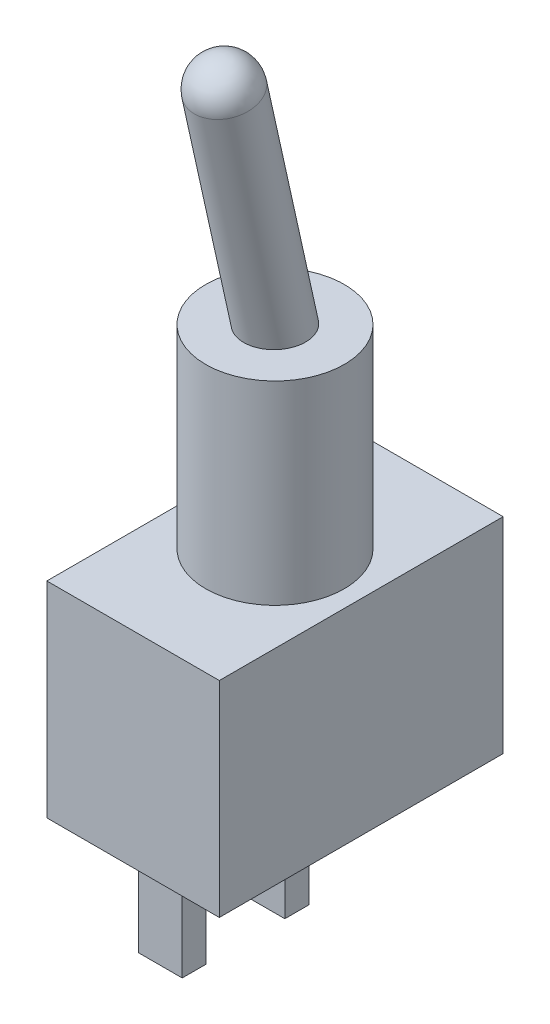
SolidWorks part; units mm, degrees
ref_plane "Front Plane" through (0, 0, 0) normal (0, 0, 1) x (1, 0, 0)
ref_plane "Top Plane" through (0, 0, 0) normal (0, 1, 0) x (1, 0, 0)
ref_plane "Right Plane" through (0, 0, 0) normal (1, 0, 0) x (0, 0, -1)
sketch "Sketch1" plane through (0, 0, 0) normal (0, 1, 0) x (1, 0, 0)
  line L1 (-3.95, 6.5) -> (3.95, 6.5)
  line L2 (-3.95, 6.5) -> (-3.95, -6.5)
  line L3 (-3.95, -6.5) -> (3.95, -6.5)
  line L4 (3.95, 6.5) -> (3.95, -6.5)
  line L5 (-3.95, 6.5) -> (3.95, -6.5) construction
  line L6 (-3.95, -6.5) -> (3.95, 6.5) construction
  point P0 (0, 0)
  dimension "D1" = 13
  dimension "D2" = 7.9
extrude "Boss-Extrude1" add sketch "Sketch1" against normal blind 9.4
sketch "Sketch2" plane through (0, -9.4, 0) normal (0, -1, 0) x (1, 0, 0)
  line L1 (-1, 5.25) -> (1, 5.25)
  line L2 (-1, 5.25) -> (-1, 4.15)
  line L3 (-1, 4.15) -> (1, 4.15)
  line L4 (1, 5.25) -> (1, 4.15)
  line L5 (-1, 5.25) -> (1, 4.15) construction
  line L6 (-1, 4.15) -> (1, 5.25) construction
  line L7 (-1, -0.55) -> (1, -0.55)
  line L8 (-1, -0.55) -> (-1, 0.55)
  line L9 (-1, 0.55) -> (1, 0.55)
  line L10 (1, -0.55) -> (1, 0.55)
  line L11 (-1, -0.55) -> (1, 0.55) construction
  line L12 (-1, 0.55) -> (1, -0.55) construction
  point P0 (0, 4.7)
  point P5 (0, 0)
  point P10 (0, 0)
  dimension "D1" = 1.1
  dimension "D2" = 2
  dimension "D3" = 4.7
extrude "Boss-Extrude2" add sketch "Sketch2" along normal blind 4.5
sketch "Sketch3" plane through (0, 0, 0) normal (0, 1, 0) x (1, 0, 0)
  circle A0 centre (0, 0) radius 3.175
  dimension "D1" = 6.35
extrude "Boss-Extrude3" add sketch "Sketch3" along normal blind 8.9
sketch "Sketch4" plane through (0, 0, 0) normal (1, 0, 0) x (0, 0, -1)
  line L0 (0, 8.9) -> (-2.3278, 19.4) construction
  line L1 (3.175, 8.9) -> (-3.175, 8.9) construction
  line L2 (0, 8.9) -> (0, 19.4) construction
  line L3 (0, 8.9) -> (1.434, 8.9)
  line L4 (1.434, 8.9) -> (-0.961, 19.703)
  line L5 (-2.6308, 20.7668) -> (0, 8.9)
  arc A0 (-0.961, 19.703) -> (-2.6308, 20.7668) centre (-2.3278, 19.4) ccw
  dimension "D3" = 2.8
  dimension "D1" = 10.5
  dimension "D2" = 12.5
revolve "Revolve1" add sketch "Sketch4" angle 360 about L5
